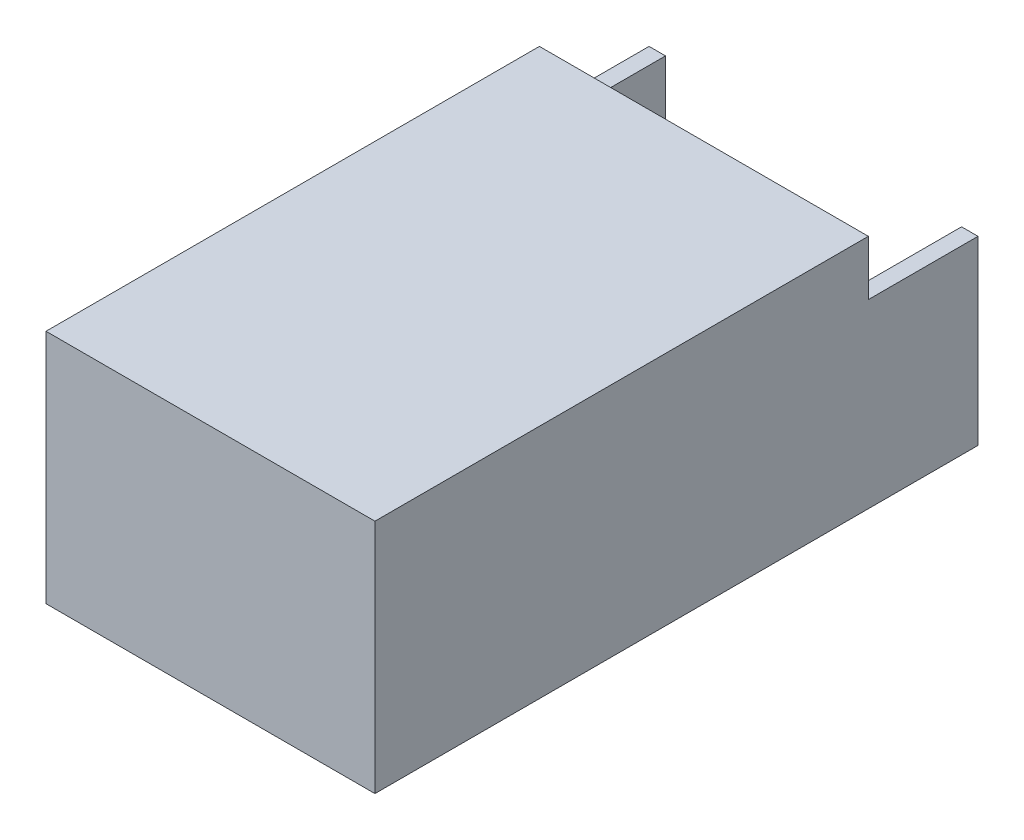
SolidWorks part; units mm, degrees
ref_plane "Ön Düzlem" through (0, 0, 0) normal (0, 0, 1) x (1, 0, 0)
ref_plane "Üst Düzlem" through (0, 0, 0) normal (0, 1, 0) x (1, 0, 0)
ref_plane "Sağ Düzlem" through (0, 0, 0) normal (1, 0, 0) x (0, 0, -1)
sketch "Çizim1" plane through (0, 0, 0) normal (0, 0, 1) x (1, 0, 0)
  line L0 (3, 3) -> (3, 40.0377)
  line L1 (0, 0) -> (60, 0)
  line L2 (0, 0) -> (0, 43.0377)
  line L3 (0, 43.0377) -> (60, 43.0377)
  line L4 (60, 0) -> (60, 43.0377)
  line L5 (3, 40.0377) -> (57, 40.0377)
  line L6 (57, 3) -> (57, 40.0377)
  line L7 (3, 3) -> (57, 3)
  dimension "D1" = 60
  dimension "D2" = 3
extrude "Yükseklik-Ekstrüzyon1" add sketch "Çizim1" along normal blind 110
sketch "Çizim2" plane through (0, 43.0377, 0) normal (0, 1, 0) x (1, 0, 0)
  line L0 (60, -110) -> (60, 0) construction
  line L1 (0, 0) -> (60, 0)
  line L2 (0, 0) -> (0, -20)
  line L3 (0, -20) -> (60, -20)
  line L4 (60, 0) -> (60, -20)
  dimension "D1" = 20
extrude "Kes-Ekstrüzyon1" cut sketch "Çizim2" against normal blind 10
sketch "Çizim3" plane through (0, 0, 110) normal (0, 0, 1) x (1, 0, 0)
  line L1 (0, 43.0377) -> (60, 43.0377)
  line L2 (0, 43.0377) -> (0, 0)
  line L3 (0, 0) -> (60, 0)
  line L4 (60, 43.0377) -> (60, 0)
extrude "Yükseklik-Ekstrüzyon2" add sketch "Çizim3" against normal blind 10
